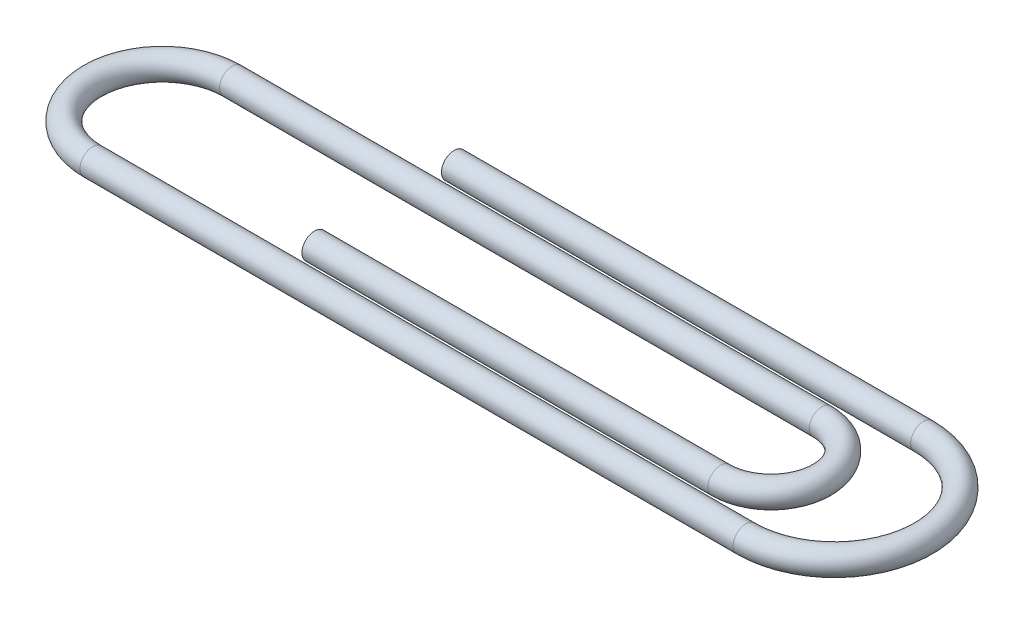
SolidWorks part; units mm, degrees
material "Plain Carbon Steel"
ref_plane "Front Plane" through (0, 0, 0) normal (0, 0, 1) x (1, 0, 0)
ref_plane "Top Plane" through (0, 0, 0) normal (0, 1, 0) x (1, 0, 0)
ref_plane "Right Plane" through (0, 0, 0) normal (1, 0, 0) x (0, 0, -1)
sketch "Sketch1" plane through (0, 0, 0) normal (0, 1, 0) x (1, 0, 0)
  line L0 (0, 0) -> (18.5, 0)
  line L1 (18.5, -7) -> (-7.25, -7)
  line L2 (-7.25, -1.5) -> (16, -1.5)
  line L3 (16, -5.5) -> (0, -5.5)
  arc A0 (18.5, 0) -> (18.5, -7) centre (18.5, -3.5) cw
  arc A1 (-7.25, -7) -> (-7.25, -1.5) centre (-7.25, -4.25) cw
  arc A2 (16, -1.5) -> (16, -5.5) centre (16, -3.5) cw
  point P2 (-10, -4.25)
  point P12 (22, -3.5)
  dimension "D1" = 10
  dimension "D4" = 3.5
  dimension "D5" = 1.5
  dimension "D2" = 32
  dimension "D3" = 4
  dimension "D6" = 1.5
sweep "Sweep1" add path "Sketch1" circular profile diameter 1 parameters "D3"=1
